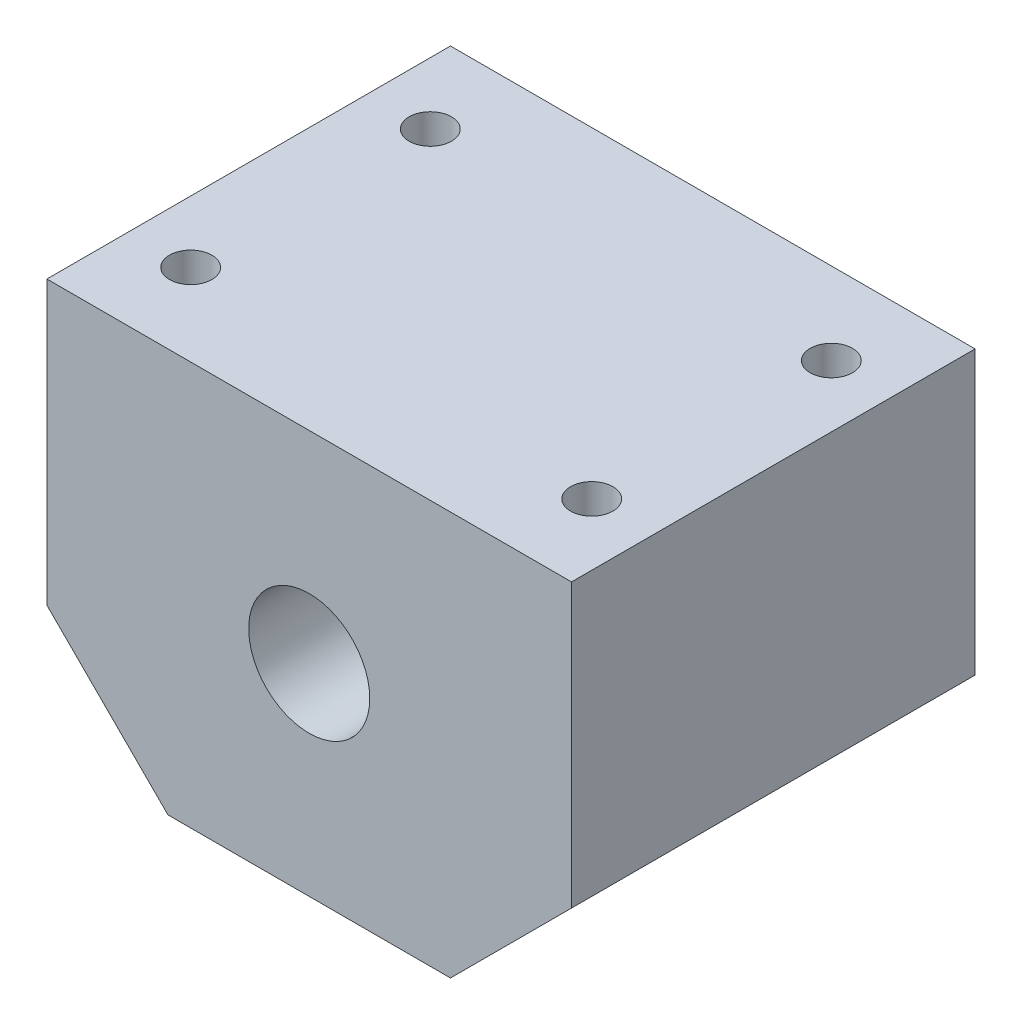
SolidWorks part; units mm, degrees
ref_plane "Front Plane" through (0, 0, 0) normal (0, 0, 1) x (1, 0, 0)
ref_plane "Top Plane" through (0, 0, 0) normal (0, 1, 0) x (1, 0, 0)
ref_plane "Right Plane" through (0, 0, 0) normal (1, 0, 0) x (0, 0, -1)
sketch "Sketch1" plane through (0, 0, 0) normal (0, 0, 1) x (1, 0, 0)
  line L0 (-26, 20) -> (-26, -8)
  line L1 (-26, -8) -> (-14, -20)
  line L2 (-14, -20) -> (14, -20)
  line L3 (-26, 20) -> (26, 20)
  line L4 (0, -55) -> (0, 55) construction
  line L5 (26, -8) -> (14, -20)
  line L6 (26, 20) -> (26, -8)
  line L7 (0, 20) -> (0, -20) construction
  circle A0 centre (0, 0) radius 6
  point P8 (0, 0)
  point P14 (12.7599, -20)
  point P15 (16.7974, -20)
  point P16 (-26, -13.4389)
  dimension "D1" = 12
  dimension "D2" = 52
  dimension "D3" = 135
  dimension "D4" = 40
  dimension "D5" = 12
extrude "Boss-Extrude1" add sketch "Sketch1" along normal mid plane 40
sketch "Sketch2" plane through (0, 20, 0) normal (0, 1, 0) x (1, 0, 0)
  line L0 (-19.875, 11.875) -> (19.875, 11.875) construction
  line L1 (-19.875, 11.875) -> (-19.875, -11.875) construction
  circle A0 centre (-19.875, 11.875) radius 2.1
  circle A1 centre (19.875, 11.875) radius 2.1
  circle A2 centre (19.875, -11.875) radius 2.1
  circle A3 centre (-19.875, -11.875) radius 2.1
  point P2 (-19.875, 0)
  point P4 (0, 11.875)
  dimension "D3" = 4.2
  dimension "D4" = 39.75
  dimension "D5" = 23.75
  dimension "D1" = 2
  dimension "D2" = 2
extrude "Cut-Extrude1" cut sketch "Sketch2" against normal blind 16
